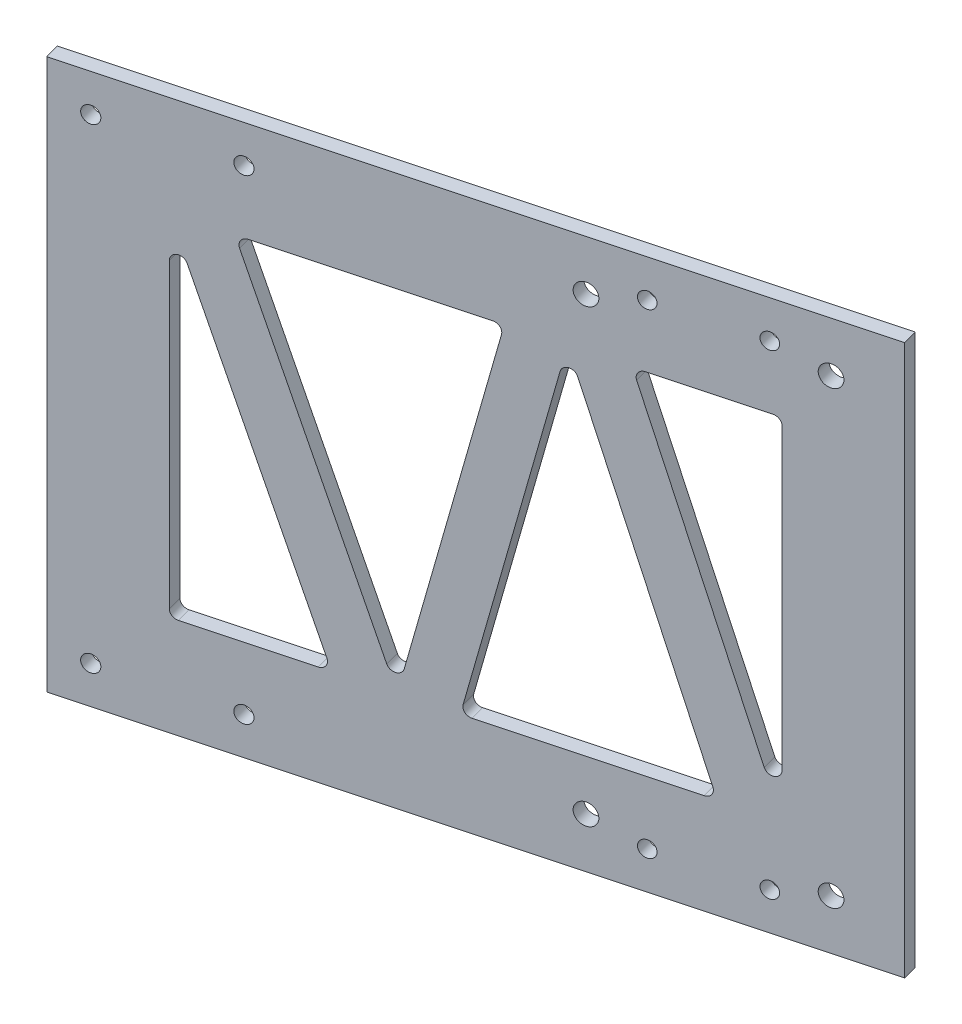
SolidWorks part; units mm, degrees
ref_plane "前视基准面" through (0, 0, 0) normal (0, 0, 1) x (1, 0, 0)
ref_plane "上视基准面" through (0, 0, 0) normal (0, 1, 0) x (1, 0, 0)
ref_plane "右视基准面" through (0, 0, 0) normal (1, 0, 0) x (0, 0, -1)
sketch "Sketch2" plane through (-8.5359, 0, -31.8565) normal (0.2588, 0, 0.9659) x (0.9659, 0, -0.2588)
  line L0 (48.5195, 100.0044) -> (48.5195, -9.9956)
  line L1 (48.5195, -9.9956) -> (188.5195, -9.9956)
  line L2 (188.5195, -9.9956) -> (188.5195, 100.0044)
  line L3 (188.5195, 100.0044) -> (48.5195, 100.0044)
  line L4 (71.4224, 72.3317) -> (94.2356, 12.0352)
  line L9 (81.3826, 80.0044) -> (121.2782, 80.0044)
  line L10 (68.5195, 71.8009) -> (68.5195, 11.5044)
  line L11 (70.0195, 10.0044) -> (92.8327, 10.0044)
  line L12 (168.5195, 78.5044) -> (168.5195, 18.8577)
  line L13 (79.9796, 77.9736) -> (104.0001, 14.4862)
  line L14 (122.7334, 78.1405) -> (106.8582, 14.6532)
  line L15 (132.2896, 75.1341) -> (116.4697, 11.8683)
  line L16 (135.161, 75.2644) -> (157.2327, 11.9985)
  line L17 (144.7942, 78.0103) -> (165.6032, 18.3636)
  line L18 (117.9249, 10.0044) -> (155.8164, 10.0044)
  line L19 (146.2104, 80.0044) -> (167.0195, 80.0044)
  arc A4 (54.0432, -2.4956) -> (57.3432, -2.4956) centre (55.6932, -2.4956) ccw construction
  arc A5 (57.3432, -2.4956) -> (54.0432, -2.4956) centre (55.6932, -2.4956) ccw construction
  arc A6 (79.0432, -2.4956) -> (82.3432, -2.4956) centre (80.6932, -2.4956) ccw construction
  arc A7 (82.3432, -2.4956) -> (79.0432, -2.4956) centre (80.6932, -2.4956) ccw construction
  arc A8 (79.0432, 92.5044) -> (82.3432, 92.5044) centre (80.6932, 92.5044) ccw construction
  arc A9 (82.3432, 92.5044) -> (79.0432, 92.5044) centre (80.6932, 92.5044) ccw construction
  arc A10 (54.0432, 92.5044) -> (57.3432, 92.5044) centre (55.6932, 92.5044) ccw construction
  arc A11 (57.3432, 92.5044) -> (54.0432, 92.5044) centre (55.6932, 92.5044) ccw construction
  arc A12 (54.0432, -2.4956) -> (57.3432, -2.4956) centre (55.6932, -2.4956) ccw
  arc A13 (57.3432, -2.4956) -> (54.0432, -2.4956) centre (55.6932, -2.4956) ccw
  arc A14 (79.0432, -2.4956) -> (82.3432, -2.4956) centre (80.6932, -2.4956) ccw
  arc A15 (82.3432, -2.4956) -> (79.0432, -2.4956) centre (80.6932, -2.4956) ccw
  arc A16 (79.0432, 92.5044) -> (82.3432, 92.5044) centre (80.6932, 92.5044) ccw
  arc A17 (82.3432, 92.5044) -> (79.0432, 92.5044) centre (80.6932, 92.5044) ccw
  arc A18 (54.0432, 92.5044) -> (57.3432, 92.5044) centre (55.6932, 92.5044) ccw
  arc A19 (57.3432, 92.5044) -> (54.0432, 92.5044) centre (55.6932, 92.5044) ccw
  circle A20 centre (166.5195, 92.5044) radius 1.6 construction
  circle A21 centre (146.5195, 92.5044) radius 1.6 construction
  circle A22 centre (146.5195, -2.4956) radius 1.6 construction
  circle A23 centre (166.5195, -2.4956) radius 1.6 construction
  circle A24 centre (176.5195, 0.0044) radius 2.1 construction
  circle A25 centre (136.5195, 0.0044) radius 2.1 construction
  circle A26 centre (176.5195, 90.0044) radius 2.1 construction
  circle A27 centre (136.5195, 90.0044) radius 2.1 construction
  circle A28 centre (166.5195, 92.5044) radius 1.6
  circle A29 centre (146.5195, 92.5044) radius 1.6
  circle A30 centre (146.5195, -2.4956) radius 1.6
  circle A31 centre (166.5195, -2.4956) radius 1.6
  circle A32 centre (176.5195, 0.0044) radius 2.1
  circle A33 centre (136.5195, 0.0044) radius 2.1
  circle A34 centre (176.5195, 90.0044) radius 2.1
  circle A35 centre (136.5195, 90.0044) radius 2.1
  arc A36 (167.0195, 80.0044) -> (168.5195, 78.5044) centre (167.0195, 78.5044) cw
  arc A37 (144.7942, 78.0103) -> (146.2104, 80.0044) centre (146.2104, 78.5044) cw
  arc A38 (165.6032, 18.3636) -> (168.5195, 18.8577) centre (167.0195, 18.8577) ccw
  arc A39 (157.2327, 11.9985) -> (155.8164, 10.0044) centre (155.8164, 11.5044) cw
  arc A40 (116.4697, 11.8683) -> (117.9249, 10.0044) centre (117.9249, 11.5044) ccw
  arc A41 (132.2896, 75.1341) -> (135.161, 75.2644) centre (133.7448, 74.7703) cw
  arc A42 (122.7334, 78.1405) -> (121.2782, 80.0044) centre (121.2782, 78.5044) ccw
  arc A43 (79.9796, 77.9736) -> (81.3826, 80.0044) centre (81.3826, 78.5044) cw
  arc A44 (104.0001, 14.4862) -> (106.8582, 14.6532) centre (105.403, 15.017) ccw
  arc A45 (94.2356, 12.0352) -> (92.8327, 10.0044) centre (92.8327, 11.5044) cw
  arc A46 (68.5195, 11.5044) -> (70.0195, 10.0044) centre (70.0195, 11.5044) ccw
  arc A47 (71.4224, 72.3317) -> (68.5195, 71.8009) centre (70.0195, 71.8009) ccw
  point P58 (123.3445, 80.0044)
  point P59 (95.004, 10.0044)
  point P64 (144.0985, 80.0044)
  point P69 (157.9284, 10.0044)
  point P72 (116.0037, 10.0044)
  point P81 (105.6958, 10.0044)
  dimension "D6" = 10
  dimension "D9" = 1.5
  dimension "D1" = 140
  dimension "D2" = 20
  dimension "D3" = 20
  dimension "D4" = 20
  dimension "D5" = 20
  dimension "D7" = 10
  dimension "D8" = 10
extrude "Extrude1" add sketch "Sketch2" along normal blind 3
